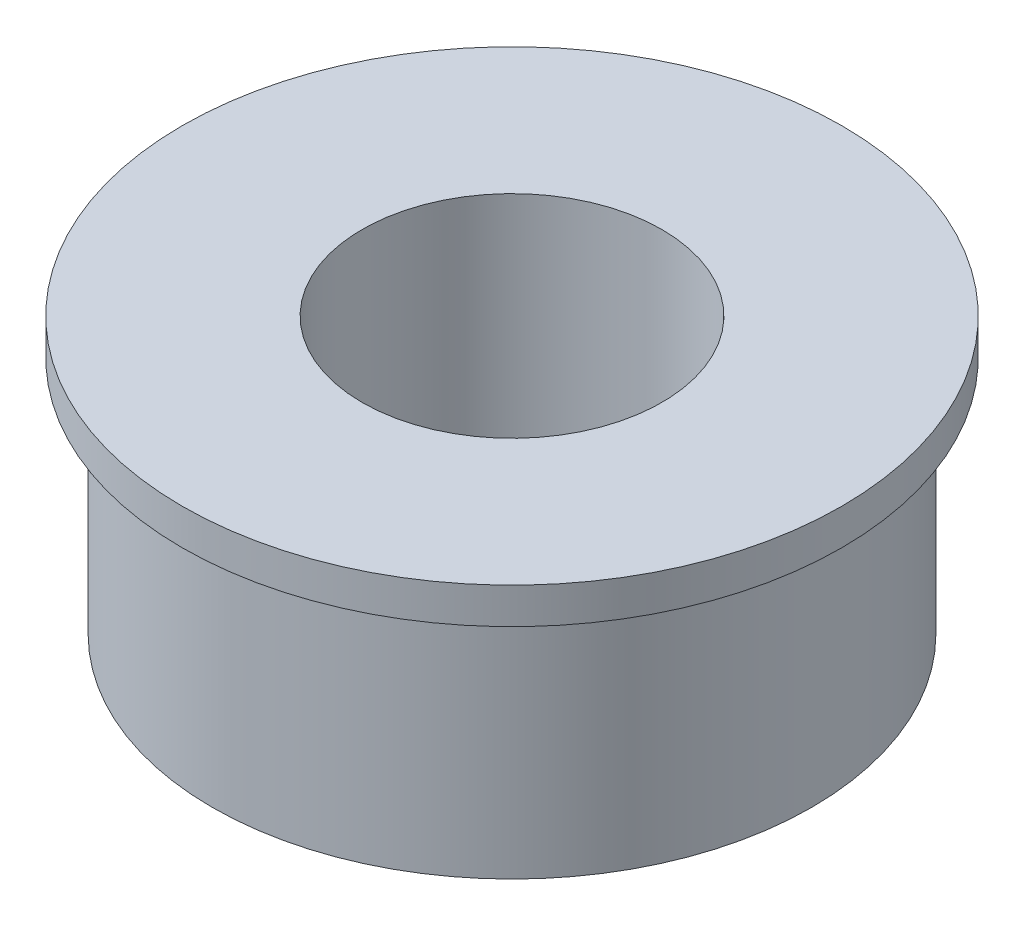
SolidWorks part; units mm, degrees
ref_plane "前视基准面" through (0, 0, 0) normal (0, 0, 1) x (1, 0, 0)
ref_plane "上视基准面" through (0, 0, 0) normal (0, 1, 0) x (1, 0, 0)
ref_plane "右视基准面" through (0, 0, 0) normal (1, 0, 0) x (0, 0, -1)
sketch "Sketch1" plane through (0, 0, 0) normal (0, 1, 0) x (1, 0, 0)
  circle A0 centre (0, 0) radius 2.5
  circle A1 centre (0, 0) radius 5
extrude "Boss-Extrude1" add sketch "Sketch1" along normal blind 4
sketch "Sketch2" plane through (0, 4, 0) normal (0, 1, 0) x (1, 0, 0)
  circle A0 centre (0, 0) radius 2.5
  circle A1 centre (0, 0) radius 5.5
extrude "Boss-Extrude2" add sketch "Sketch2" along normal blind 0.6
